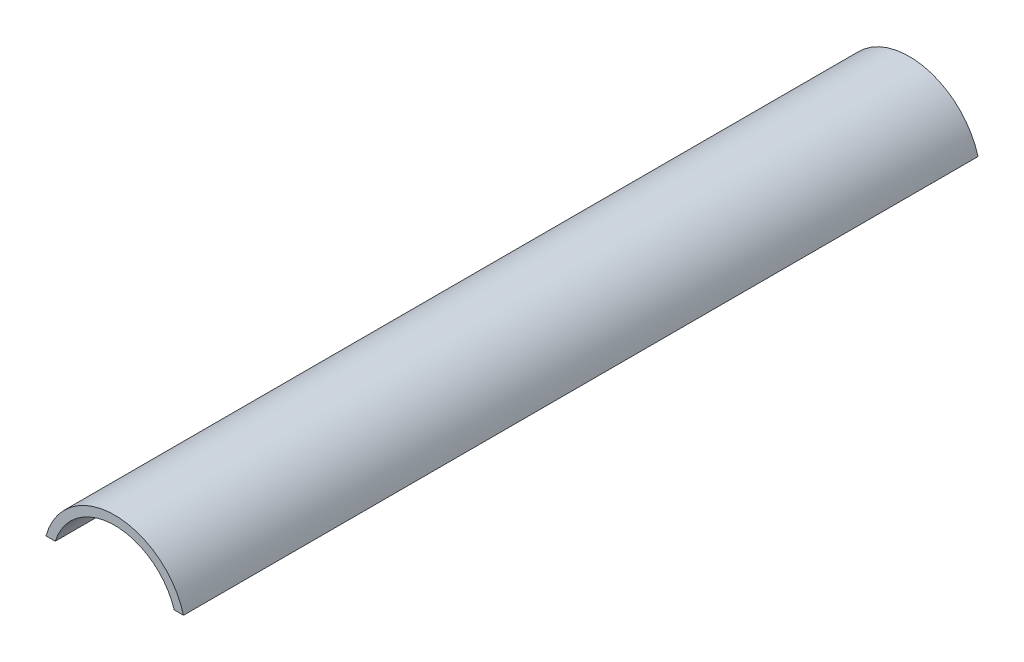
SolidWorks part; units mm, degrees
material "Commercial Bronze, UNS C22000 (90-10 Bronze)"
ref_plane "Front Plane" through (0, 0, 0) normal (0, 0, 1) x (1, 0, 0)
ref_plane "Top Plane" through (0, 0, 0) normal (0, 1, 0) x (1, 0, 0)
ref_plane "Right Plane" through (0, 0, 0) normal (1, 0, 0) x (0, 0, -1)
sketch "Sketch1" plane through (0, 0, 0) normal (0, 0, 1) x (1, 0, 0)
  line L0 (-12.2446, 3.3705) -> (-10.5969, 3.3705)
  line L1 (10.5969, 3.3705) -> (12.2446, 3.3705)
  arc A0 (12.2446, 3.3705) -> (-12.2446, 3.3705) centre (0, 0) ccw
  arc A1 (10.5969, 3.3705) -> (-10.5969, 3.3705) centre (0, 0) ccw
  circle A2 centre (0, 0) radius 12.7 construction
  circle A3 centre (0, 0) radius 11.12 construction
  dimension "D1" = 25.4
  dimension "D2" = 1.58
extrude "Boss-Extrude1" add sketch "Sketch1" along normal blind 141.5
